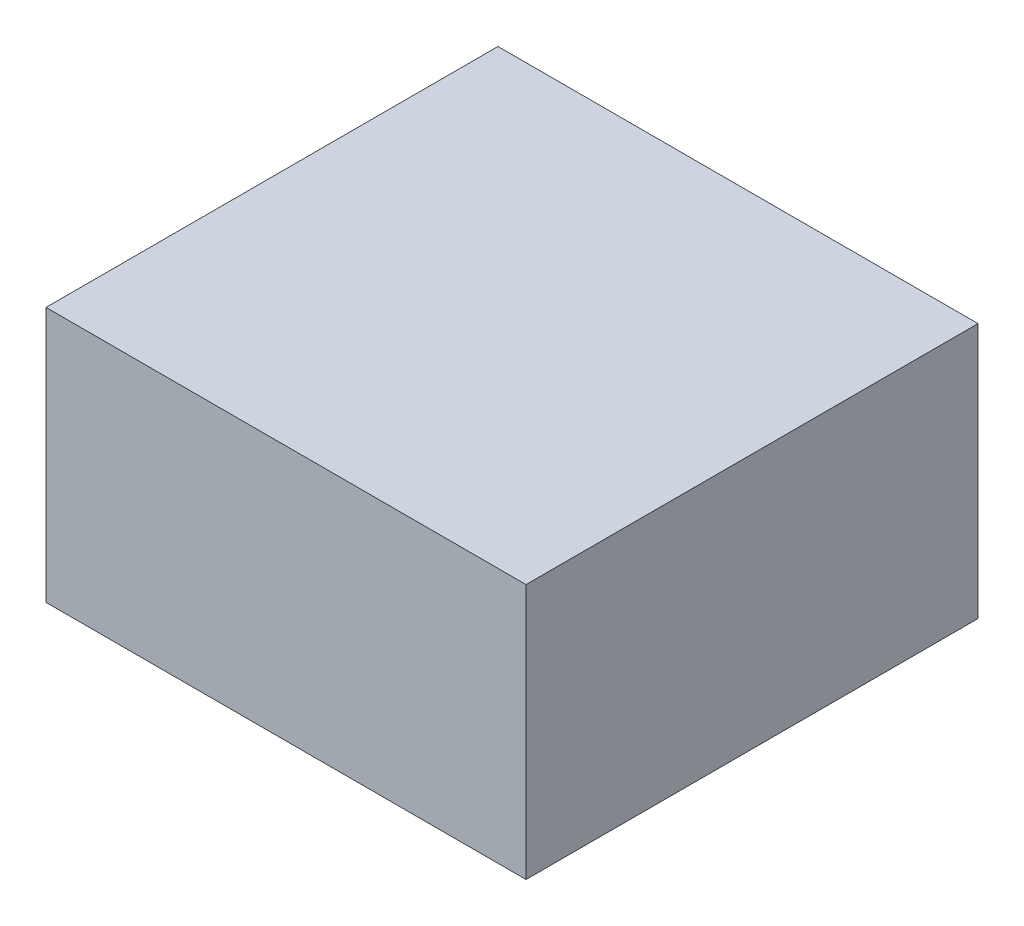
SolidWorks part; units mm, degrees
ref_plane "Спереди" through (0, 0, 0) normal (0, 0, 1) x (1, 0, 0)
ref_plane "Сверху" through (0, 0, 0) normal (0, 1, 0) x (1, 0, 0)
ref_plane "Справа" through (0, 0, 0) normal (1, 0, 0) x (0, 0, -1)
sketch "Эскиз1" plane through (0, 0, 0) normal (0, 1, 0) x (1, 0, 0)
  line L1 (0, 0) -> (171, 0)
  line L2 (0, 0) -> (0, -161)
  line L3 (0, -161) -> (171, -161)
  line L4 (171, 0) -> (171, -161)
  dimension "D1" = 171
  dimension "D2" = 161
extrude "Бобышка-Вытянуть1" add sketch "Эскиз1" along normal blind 91
